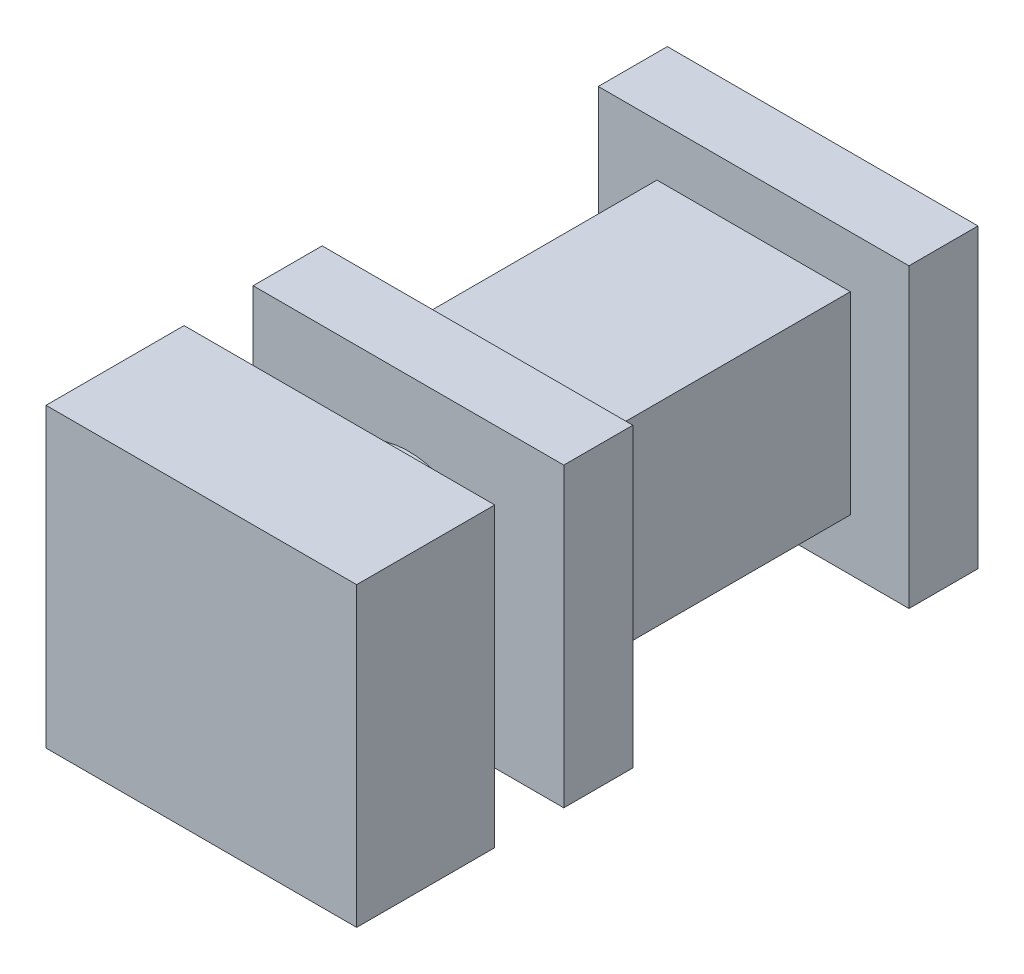
SolidWorks part; units mm, degrees
ref_plane "前视基准面" through (0, 0, 0) normal (0, 0, 1) x (1, 0, 0)
ref_plane "上视基准面" through (0, 0, 0) normal (0, 1, 0) x (1, 0, 0)
ref_plane "右视基准面" through (0, 0, 0) normal (1, 0, 0) x (0, 0, -1)
sketch "草图2" plane through (0, 0, 0) normal (0, 0, 1) x (1, 0, 0)
  line L9 (-1.125, -1.075) -> (1.125, -1.075)
  line L10 (-1.125, -1.075) -> (-1.125, 1.075)
  line L11 (-1.125, 1.075) -> (1.125, 1.075)
  line L12 (1.125, -1.075) -> (1.125, 1.075)
  line L13 (-1.125, -1.075) -> (1.125, 1.075) construction
  line L14 (-1.125, 1.075) -> (1.125, -1.075) construction
  point P0 (0, 0)
  dimension "D1" = 2.15
  dimension "D2" = 2.25
extrude "凸台-拉伸4" add sketch "草图2" along normal blind 1
sketch "草图4" plane through (0, 0, 0) normal (0, 0, -1) x (-1, 0, 0)
  circle A0 centre (0, 0) radius 0.6
  dimension "D1" = 1.2
extrude "凸台-拉伸5" add sketch "草图4" along normal blind 0.5
sketch "草图5" plane through (0, 0, -0.5) normal (0, 0, -1) x (-1, 0, 0)
  line L1 (-1.125, -1.075) -> (1.125, -1.075)
  line L2 (-1.125, -1.075) -> (-1.125, 1.075)
  line L3 (-1.125, 1.075) -> (1.125, 1.075)
  line L4 (1.125, -1.075) -> (1.125, 1.075)
  line L5 (-1.125, -1.075) -> (1.125, 1.075) construction
  line L6 (-1.125, 1.075) -> (1.125, -1.075) construction
  point P0 (0, 0)
  dimension "D1" = 2.15
  dimension "D2" = 2.25
extrude "凸台-拉伸6" add sketch "草图5" along normal blind 0.5
sketch "草图9" plane through (0, 0, -1) normal (0, 0, -1) x (-1, 0, 0)
  line L1 (-0.7, -0.7) -> (0.7, -0.7)
  line L2 (-0.7, -0.7) -> (-0.7, 0.7)
  line L3 (-0.7, 0.7) -> (0.7, 0.7)
  line L4 (0.7, -0.7) -> (0.7, 0.7)
  line L5 (-0.7, -0.7) -> (0.7, 0.7) construction
  line L6 (-0.7, 0.7) -> (0.7, -0.7) construction
  point P0 (0, 0)
  dimension "D1" = 1.4
extrude "凸台-拉伸7" add sketch "草图9" along normal blind 2
sketch "草图10" plane through (0, 0, -3) normal (0, 0, -1) x (-1, 0, 0)
  line L1 (-1.125, -1.075) -> (1.125, -1.075)
  line L2 (-1.125, -1.075) -> (-1.125, 1.075)
  line L3 (-1.125, 1.075) -> (1.125, 1.075)
  line L4 (1.125, -1.075) -> (1.125, 1.075)
  line L5 (-1.125, -1.075) -> (1.125, 1.075) construction
  line L6 (-1.125, 1.075) -> (1.125, -1.075) construction
  point P0 (0, 0)
extrude "凸台-拉伸8" add sketch "草图10" along normal blind 0.5
